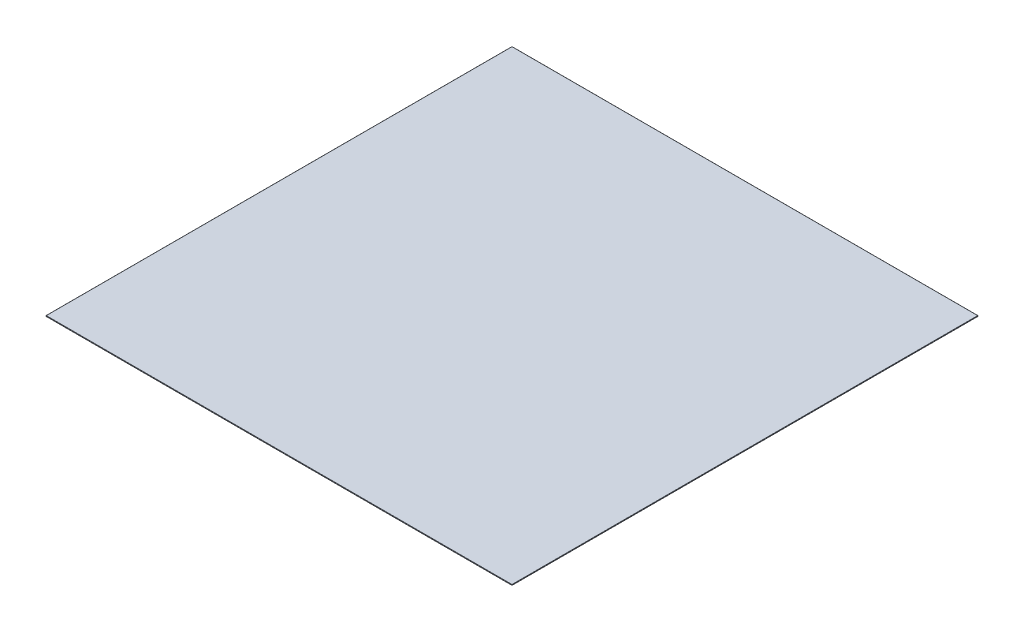
SolidWorks part; units mm, degrees
material "6061-T6 (SS)"
ref_plane "Front Plane" through (0, 0, 0) normal (0, 0, 1) x (1, 0, 0)
ref_plane "Top Plane" through (0, 0, 0) normal (0, 1, 0) x (1, 0, 0)
ref_plane "Right Plane" through (0, 0, 0) normal (1, 0, 0) x (0, 0, -1)
sketch "Sketch1" plane through (0, 0, 0) normal (0, 1, 0) x (1, 0, 0)
  line L1 (0, 0) -> (2000, 0)
  line L2 (0, 0) -> (0, -2000)
  line L3 (0, -2000) -> (2000, -2000)
  line L4 (2000, 0) -> (2000, -2000)
  dimension "D1" = 2000
  dimension "D2" = 2000
extrude "Boss-Extrude1" add sketch "Sketch1" along normal blind 3.175
sketch "Sketch3" plane through (0, 0, 0) normal (0, -1, 0) x (1, 0, 0)
  line L0 (0, 2000) -> (2000, 0) construction
  line L1 (0, 0) -> (2000, 2000) construction
  line L3 (2000, 0) -> (0, 0) construction
  line L5 (2000, 2000) -> (2000, 0) construction
  line L7 (0, 0) -> (0, 2000) construction
  line L9 (0, 2000) -> (2000, 2000) construction
  line L10 (1000, 500) -> (1000, 0) construction
  line L11 (1500, 1000) -> (2000, 1000)
  line L12 (500, 1000) -> (0, 1000)
  line L13 (1000, 1500) -> (1000, 2000)
  point P8 (1000, 1000)
  point P9 (1000, 250)
  point P13 (1000, 500)
  point P23 (1500, 1000)
  point P24 (500, 1000)
  point P25 (1000, 1500)
  point P30 (250, 1000)
  point P31 (1000, 1750)
  point P32 (1750, 1000)
fillet "Fillet1" radius 1 12 edges at (0, 1.5875, 2000) (2000, 1.5875, 2000) (2000, 1.5875, 0) (0, 1.5875, 0) (1000, 3.175, 0) (2000, 3.175, 1000) (1000, 3.175, 2000) (0, 3.175, 1000) (1000, 0, 2000) (2000, 0, 1000) (1000, 0, 0) (0, 0, 1000)
